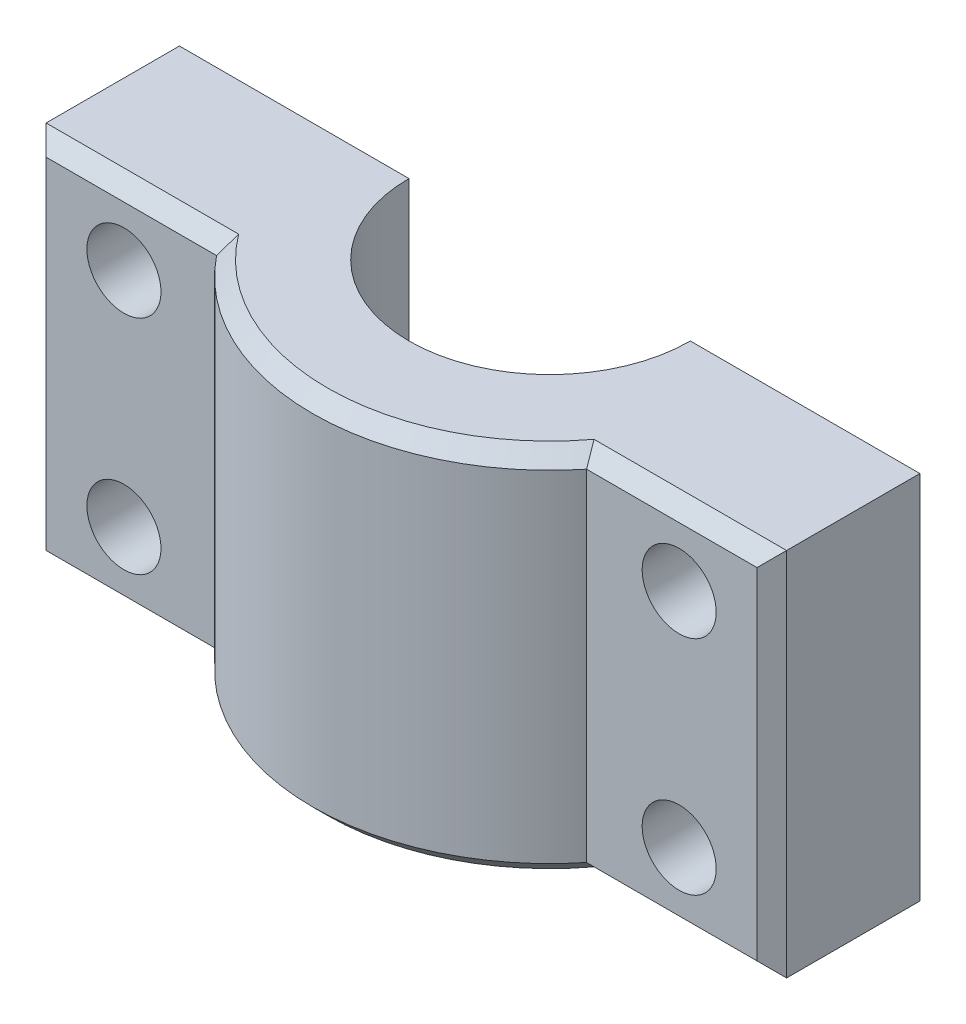
SolidWorks part; units mm, degrees
ref_plane "Front" through (0, 0, 0) normal (0, 0, 1) x (1, 0, 0)
ref_plane "Top" through (0, 0, 0) normal (0, 1, 0) x (1, 0, 0)
ref_plane "Right" through (0, 0, 0) normal (1, 0, 0) x (0, 0, -1)
sketch "草图1" plane through (0, 0, 0) normal (0, 1, 0) x (1, 0, 0)
  circle A0 centre (0, 0) radius 8
  dimension "D1" = 16
extrude "凸台-拉伸1" add sketch "草图1" along normal blind 12.5
sketch "草图3" plane through (0, 12.5, 0) normal (0, 1, 0) x (1, 0, 0)
  line L1 (12.5, 5) -> (-12.5, 5)
  line L2 (12.5, 5) -> (12.5, -5)
  line L3 (12.5, -5) -> (-12.5, -5)
  line L4 (-12.5, 5) -> (-12.5, -5)
  line L5 (12.5, 5) -> (-12.5, -5) construction
  line L6 (12.5, -5) -> (-12.5, 5) construction
  point P0 (0, 0)
  dimension "D1" = 25
  dimension "D2" = 10
extrude "凸台-拉伸2" add sketch "草图3" against normal up to surface (12.5 mm away) up to face at (0, 0, 8)
sketch "草图4" plane through (0, 12.5, 0) normal (0, 1, 0) x (1, 0, 0)
  circle A0 centre (0, 0) radius 4.75
  dimension "D1" = 9.5
extrude "切除-拉伸1" cut sketch "草图4" against normal through all
sketch "草图5" plane through (0, 0, -5) normal (0, 0, -1) x (-1, 0, 0)
  line L0 (9.3725, 0) -> (9.3725, 12.5) construction
  line L1 (12.5, 0) -> (6.245, 0) construction
  line L2 (6.245, 12.5) -> (12.5, 12.5) construction
  line L3 (6.245, 6.25) -> (12.5, 6.25) construction
  line L6 (6.245, 0) -> (6.245, 12.5) construction
  line L7 (12.5, 0) -> (12.5, 12.5) construction
  circle A0 centre (9.3725, 2.5) radius 1.25
  circle A1 centre (9.3725, 10) radius 1.25
  dimension "D1" = 2.5
  dimension "D2" = 2.5
  dimension "D3" = 7.5
extrude "切除-拉伸2" cut sketch "草图5" against normal through all
mirror "镜向1" about plane through (0, 0, 0) normal (1, 0, 0) of "切除-拉伸2"
chamfer "倒角1" distance 0.5 angle 45 16 edges at (12.5, 6.25, 5) (12.5, 6.25, -5) (-12.5, 6.25, 5) (-12.5, 6.25, -5) (9.3725, 12.5, 5) (0, 12.5, 8) (0, 0, 8) (-9.3725, 12.5, 5) (9.3725, 0, 5) (-9.3725, 0, 5) (-9.3725, 0, -5) (0, 12.5, -8) (0, 0, -8) (9.3725, 0, -5) (9.3725, 12.5, -5) (-9.3725, 12.5, -5)
sketch "草图6" plane through (0, 0, 0) normal (0, 0, 1) x (1, 0, 0)
  line L1 (24.5805, 23.2005) -> (-24.5805, 23.2005)
  line L2 (24.5805, 23.2005) -> (24.5805, -23.2005)
  line L3 (24.5805, -23.2005) -> (-24.5805, -23.2005)
  line L4 (-24.5805, 23.2005) -> (-24.5805, -23.2005)
  line L5 (24.5805, 23.2005) -> (-24.5805, -23.2005) construction
  line L6 (24.5805, -23.2005) -> (-24.5805, 23.2005) construction
  point P0 (0, 0)
extrude "切除-拉伸3" cut sketch "草图6" against normal through all
